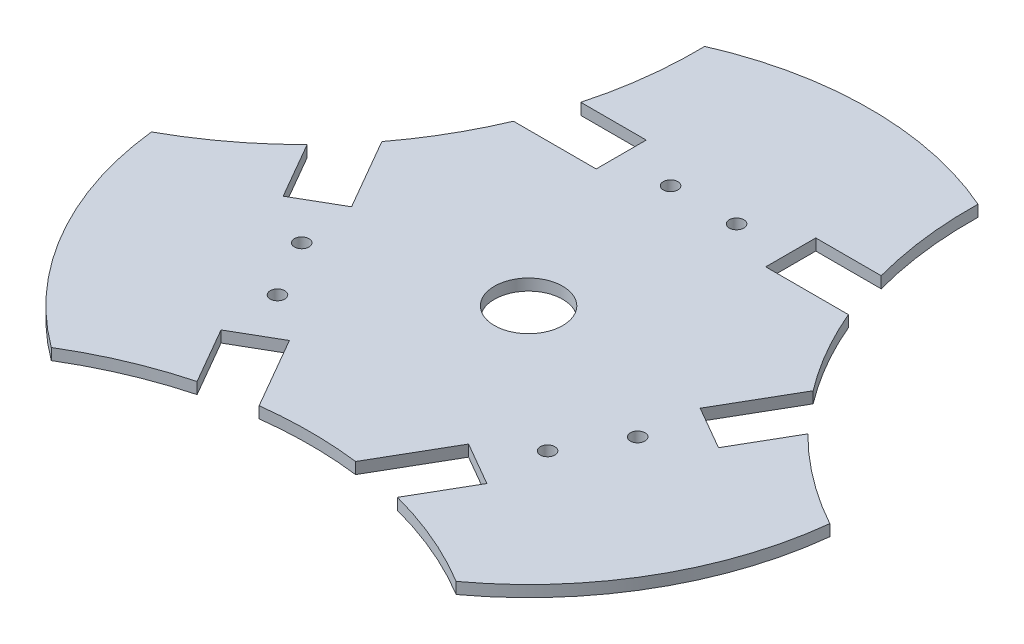
SolidWorks part; units mm, degrees
ref_plane "Plan de face" through (0, 0, 0) normal (0, 0, 1) x (1, 0, 0)
ref_plane "Plan de dessus" through (0, 0, 0) normal (0, 1, 0) x (1, 0, 0)
ref_plane "Plan de droite" through (0, 0, 0) normal (1, 0, 0) x (0, 0, -1)
sketch "Esquisse1" plane through (0, 0, 0) normal (0, 1, 0) x (1, 0, 0)
  line L0 (88.9553, -120.7765) -> (59.3489, -51.0192) construction
  line L1 (59.3489, -51.0192) -> (73.852, -25.9063) construction
  line L2 (73.852, -25.9063) -> (149.069, -16.6861) construction
  line L3 (-149.069, -16.6861) -> (-73.8477, -25.8709) construction
  line L4 (-73.8477, -25.8709) -> (-59.3539, -50.9892) construction
  line L5 (-59.3539, -50.9892) -> (-89.0447, -120.7106) construction
  line L6 (-89.0447, -120.7106) -> (-149.069, -16.6861) construction
  line L7 (149.069, -16.6861) -> (88.9553, -120.7765) construction
  line L8 (60.05, 137.4554) -> (-60.05, 137.4554) construction
  line L9 (-60.05, 137.4554) -> (-14.5, 76.893) construction
  line L10 (-14.5, 76.893) -> (14.5, 76.893) construction
  line L11 (14.5, 76.893) -> (60.05, 137.4554) construction
  line L12 (-73.8477, -25.8709) -> (-82.5092, -30.8688) construction
  line L13 (-43.3986, -80.7575) -> (-34.9181, -69.6561) construction
  line L26 (-119.0569, -68.6983) -> (-66.6008, -38.4301) construction
  line L36 (59.3489, -51.0192) -> (68.0086, -56.0203) construction
  line L37 (59.3489, -51.0192) -> (34.9298, -69.7028) construction
  line L44 (119.0122, -68.7313) -> (66.6005, -38.4628) construction
  line L50 (14.5, 76.893) -> (14.5, 86.893) construction
  line L51 (-34.9181, -69.6561) -> (-59.3539, -50.9892) construction
  line L58 (0, 137.4554) -> (0, 76.893) construction
  line L64 (73.852, -25.9063) -> (77.8304, 4.5821) construction
  line L65 (77.8304, 4.5821) -> (91.68, 2.7749) construction
  line L66 (95.7044, -12.2518) -> (76.6532, -1.2495)
  line L72 (95.7044, -12.2518) -> (106.7068, 6.7994)
  line L73 (76.6532, -1.2495) -> (87.6556, 17.8017)
  line L75 (87.6556, 17.8017) -> (95.7044, -12.2518) construction
  line L76 (106.7068, 6.7994) -> (76.6532, -1.2495) construction
  line L77 (106.7068, 6.7994) -> (110.089, 12.6559)
  line L78 (87.6556, 17.8017) -> (94.8268, 30.2191)
  line L79 (34.9298, -69.7028) -> (43.4169, -80.7954) construction
  line L80 (28.3901, -84.8198) -> (58.4437, -76.771) construction
  line L81 (47.4413, -95.8222) -> (39.3925, -65.7686) construction
  line L82 (58.4437, -76.771) -> (39.3925, -65.7686)
  line L83 (39.3925, -65.7686) -> (28.3901, -84.8198)
  line L84 (28.3901, -84.8198) -> (21.2189, -97.2372)
  line L85 (58.4437, -76.771) -> (47.4413, -95.8222)
  line L86 (47.4413, -95.8222) -> (44.0591, -101.6787)
  line L87 (-39.3686, -65.7323) -> (-28.3733, -84.7875)
  line L88 (-39.3686, -65.7323) -> (-58.4239, -76.7276)
  line L90 (-58.4239, -76.7276) -> (-47.4286, -95.7828)
  line L91 (-39.3686, -65.7323) -> (-47.4286, -95.7828) construction
  line L92 (-58.4239, -76.7276) -> (-28.3733, -84.7875) construction
  line L93 (-47.4286, -95.7828) -> (-44.0572, -101.6257)
  line L94 (-28.3733, -84.7875) -> (-21.2049, -97.2108)
  line L95 (-95.666, -12.1856) -> (-87.606, 17.865) construction
  line L96 (-76.6107, -1.1903) -> (-106.6613, 6.8697) construction
  line L97 (-106.6613, 6.8697) -> (-110.0327, 12.7125)
  line L98 (-95.666, -12.1856) -> (-106.6613, 6.8697)
  line L99 (-76.6107, -1.1903) -> (-95.666, -12.1856)
  line L100 (-76.6107, -1.1903) -> (-87.606, 17.865)
  line L101 (-87.606, 17.865) -> (-94.7745, 30.2882)
  line L106 (-59.2539, 88.9537) -> (-37.2539, 88.9537)
  line L108 (-37.2539, 88.9537) -> (-37.2539, 66.9537)
  line L109 (-59.2539, 66.9537) -> (-37.2539, 66.9537)
  line L115 (-37.2539, 88.9537) -> (-59.2539, 66.9537) construction
  line L116 (-59.2539, 88.9537) -> (-37.2539, 66.9537) construction
  line L119 (-48.2539, 77.9537) -> (-42.8796, 65.0621) construction
  line L120 (-42.8796, 65.0621) -> (-14.5, 76.893) construction
  line L121 (-59.2539, 66.9537) -> (-73.6, 66.9537)
  line L122 (-59.2539, 88.9537) -> (-66.0031, 88.9537)
  line L123 (48.2539, 77.9537) -> (42.8796, 65.0621) construction
  line L124 (42.8796, 65.0621) -> (14.5, 76.893) construction
  line L125 (37.2539, 88.9537) -> (59.2539, 66.9537) construction
  line L126 (59.2539, 88.9537) -> (37.2539, 66.9537) construction
  line L127 (37.2539, 88.9537) -> (37.2539, 66.9537)
  line L128 (59.2539, 88.9537) -> (66.0031, 88.9537)
  line L129 (59.2539, 66.9537) -> (37.2539, 66.9537)
  line L130 (59.2539, 66.9537) -> (73.6, 66.9537)
  line L131 (59.2539, 88.9537) -> (37.2539, 88.9537)
  arc A0 (-149.069, -16.6861) -> (-89.0447, -120.7106) centre (0, 0) ccw
  circle A4 centre (14.5, 76.893) radius 3.2
  circle A5 centre (-14.5, 76.893) radius 3.2
  circle A6 centre (-73.8477, -25.8709) radius 3.2
  circle A7 centre (-59.3539, -50.9892) radius 3.2
  circle A8 centre (59.3489, -51.0192) radius 3.2
  circle A9 centre (73.852, -25.9063) radius 3.2
  circle A10 centre (0, 0) radius 15
  arc A12 (88.9553, -120.7765) -> (149.069, -16.6861) centre (0, 0) ccw
  arc A13 (60.05, 137.4554) -> (-60.05, 137.4554) centre (0, 0) ccw
  circle A19 centre (91.68, 2.7749) radius 3 construction
  circle A21 centre (43.4169, -80.7954) radius 3 construction
  circle A23 centre (-43.3986, -80.7575) radius 3 construction
  arc A24 (88.9553, -120.7765) -> (44.0591, -101.6787) centre (-0.0992, -267.8102) ccw
  arc A25 (21.2189, -97.2372) -> (-21.2049, -97.2108) centre (-0.0992, -267.8102) ccw
  arc A26 (-44.0572, -101.6257) -> (-89.0447, -120.7106) centre (-0.0992, -267.8102) ccw
  circle A27 centre (-91.636, 2.8397) radius 3 construction
  circle A37 centre (-48.2539, 77.9537) radius 3.7858 construction
  arc A38 (-149.069, -16.6861) -> (-110.0327, 12.7125) centre (-231.9139, 133.9337) ccw
  arc A39 (-66.0031, 88.9537) -> (-60.05, 137.4554) centre (-231.9139, 133.9337) ccw
  circle A40 centre (48.2539, 77.9537) radius 3.7858 construction
  arc A41 (60.05, 137.4554) -> (66.0031, 88.9537) centre (231.9139, 133.9337) ccw
  arc A42 (73.6, 66.9537) -> (94.8268, 30.2191) centre (231.9139, 133.9337) ccw
  arc A43 (-94.7745, 30.2882) -> (-73.6, 66.9537) centre (-231.9139, 133.9337) ccw
  arc A44 (110.089, 12.6559) -> (149.069, -16.6861) centre (231.9139, 133.9337) ccw
  point P1 (-43.3986, -80.7575)
  point P27 (-48.2539, 77.9537)
  point P49 (91.68, 2.7749)
  point P51 (-62.6285, 88.9537)
  point P91 (62.6285, 88.9537)
  dimension "D1" = 300
  dimension "D5" = 171.9
  dimension "D6" = 171.9
  dimension "D7" = 171.9
  dimension "D9" = 120.1
  dimension "D12" = 6.4
  dimension "D13" = 30
  dimension "D32" = 6
  dimension "D20" = 6
  dimension "D2" = 178
  dimension "D3" = 178
  dimension "D4" = 178
  dimension "D8" = 120.1
  dimension "D10" = 75.78
  dimension "D11" = 29
  dimension "D14" = 10
  dimension "D15" = 91.68
  dimension "D16" = 29
  dimension "D17" = 30.75
  dimension "D18" = 10
  dimension "D19" = 13.97
  dimension "D21" = 22
  dimension "D22" = 10
  dimension "D23" = 22
  dimension "D24" = 22
  dimension "D25" = 22
  dimension "D26" = 29
  dimension "D27" = 30.7469
  dimension "D28" = 13.967
  dimension "D29" = 30.7469
  dimension "D30" = 22
  dimension "D31" = 91.68
  dimension "D33" = 13.967
  dimension "D34" = 91.68
extrude "Boss.-Extru.1" add sketch "Esquisse1" along normal blind 5
